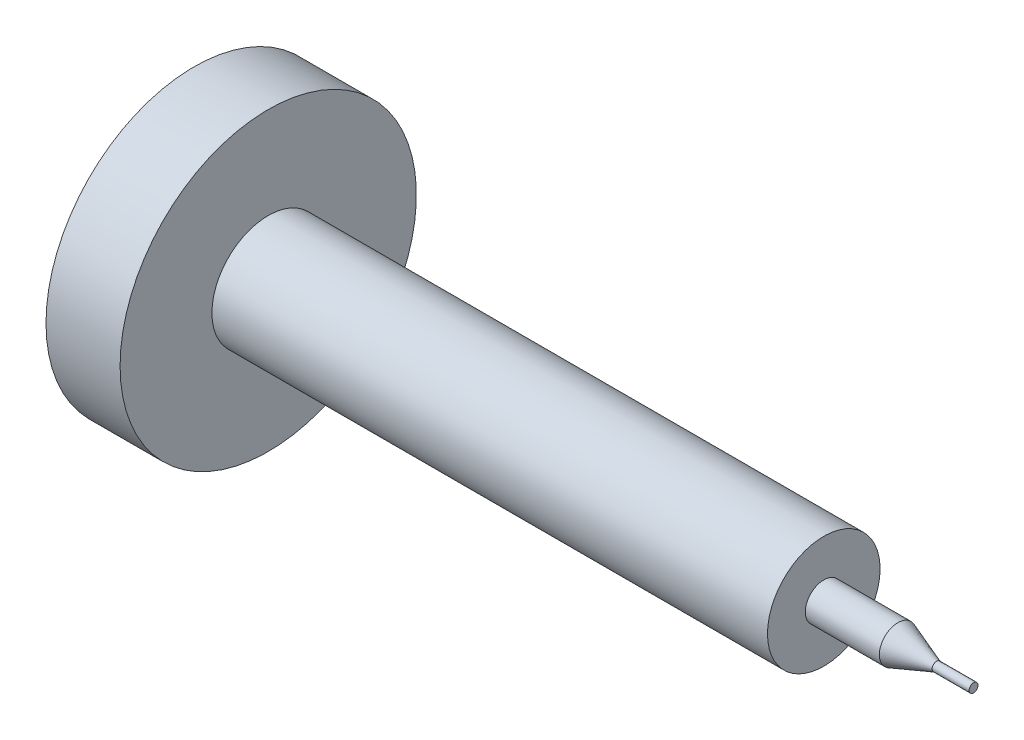
SolidWorks part; units mm, degrees
ref_plane "Front Plane" through (0, 0, 0) normal (0, 0, 1) x (1, 0, 0)
ref_plane "Top Plane" through (0, 0, 0) normal (0, 1, 0) x (1, 0, 0)
ref_plane "Right Plane" through (0, 0, 0) normal (1, 0, 0) x (0, 0, -1)
sketch "Sketch1" plane through (0, 0, 0) normal (0, 0, 1) x (1, 0, 0)
  line L0 (0, 0) -> (13.2167, 0) construction
  line L1 (0, 0) -> (0, 6.35)
  line L2 (0, 6.35) -> (3.175, 6.35)
  line L3 (3.175, 6.35) -> (3.175, 2.413)
  line L4 (3.175, 2.413) -> (26.9875, 2.413)
  line L5 (26.9875, 2.413) -> (26.9875, 0.7937)
  line L6 (26.9875, 0.7937) -> (30.1625, 0.7937)
  line L7 (30.1625, 0.7937) -> (31.8199, 0.1905)
  line L8 (31.8199, 0.1905) -> (33.4074, 0.1905)
  line L9 (33.4074, 0.1905) -> (33.4074, 0)
  line L10 (0, 0) -> (33.4074, 0)
  point P6 (34.18, 0.2386)
  dimension "D1" = 12.7
  dimension "D2" = 3.175
  dimension "D3" = 23.8125
  dimension "D4" = 4.826
  dimension "D5" = 1.5875
  dimension "D6" = 3.175
  dimension "D7" = 0.381
  dimension "D8" = 20
  dimension "D9" = 1.5875
revolve "Revolve1" add sketch "Sketch1" angle 360 about L0
cosmetic thread "Cosmetic Thread1" parameters "D1"=14.2875, "D2"=3.5662
